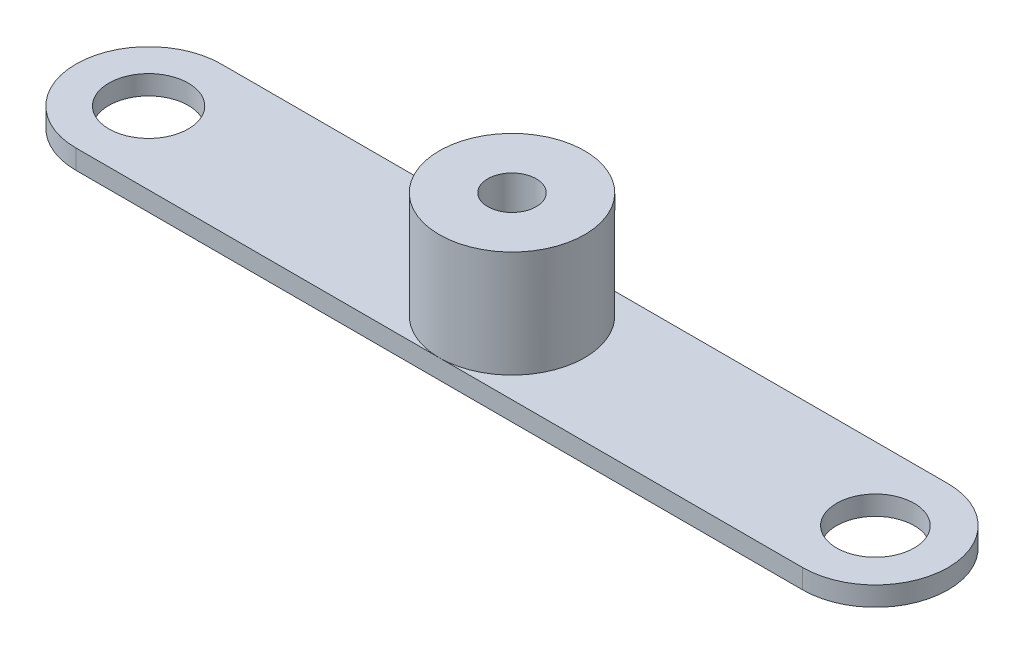
SolidWorks part; units mm, degrees
ref_plane "Front Plane" through (0, 0, 0) normal (0, 0, 1) x (1, 0, 0)
ref_plane "Top Plane" through (0, 0, 0) normal (0, 1, 0) x (1, 0, 0)
ref_plane "Right Plane" through (0, 0, 0) normal (1, 0, 0) x (0, 0, -1)
sketch "Sketch1" plane through (0, 0, 0) normal (0, 1, 0) x (1, 0, 0)
  line L0 (-37.5, 0) -> (37.5, 0) construction
  line L1 (-37.5, 7.5) -> (37.5, 7.5)
  line L2 (-37.5, -7.5) -> (37.5, -7.5)
  arc A0 (-37.5, 7.5) -> (-37.5, -7.5) centre (-37.5, 0) ccw
  arc A1 (37.5, -7.5) -> (37.5, 7.5) centre (37.5, 0) ccw
  circle A2 centre (-37.5, 0) radius 4.1
  circle A3 centre (37.5, 0) radius 4
  point P2 (0, 0)
  dimension "D2" = 7.5
  dimension "D3" = 4.1
  dimension "D4" = 4
  dimension "D1" = 75
extrude "Boss-Extrude1" add sketch "Sketch1" along normal blind 2
sketch "Sketch3" plane through (0, 2, 0) normal (0, 1, 0) x (1, 0, 0)
  circle A0 centre (0, 0) radius 7.5
  dimension "D1" = 7.5
extrude "Boss-Extrude3" add sketch "Sketch3" along normal blind 11
sketch "Sketch4" plane through (0, 13, 0) normal (0, 1, 0) x (1, 0, 0)
  circle A0 centre (0, 0) radius 2.5
  dimension "D1" = 5
extrude "Cut-Extrude1" cut sketch "Sketch4" against normal through all
